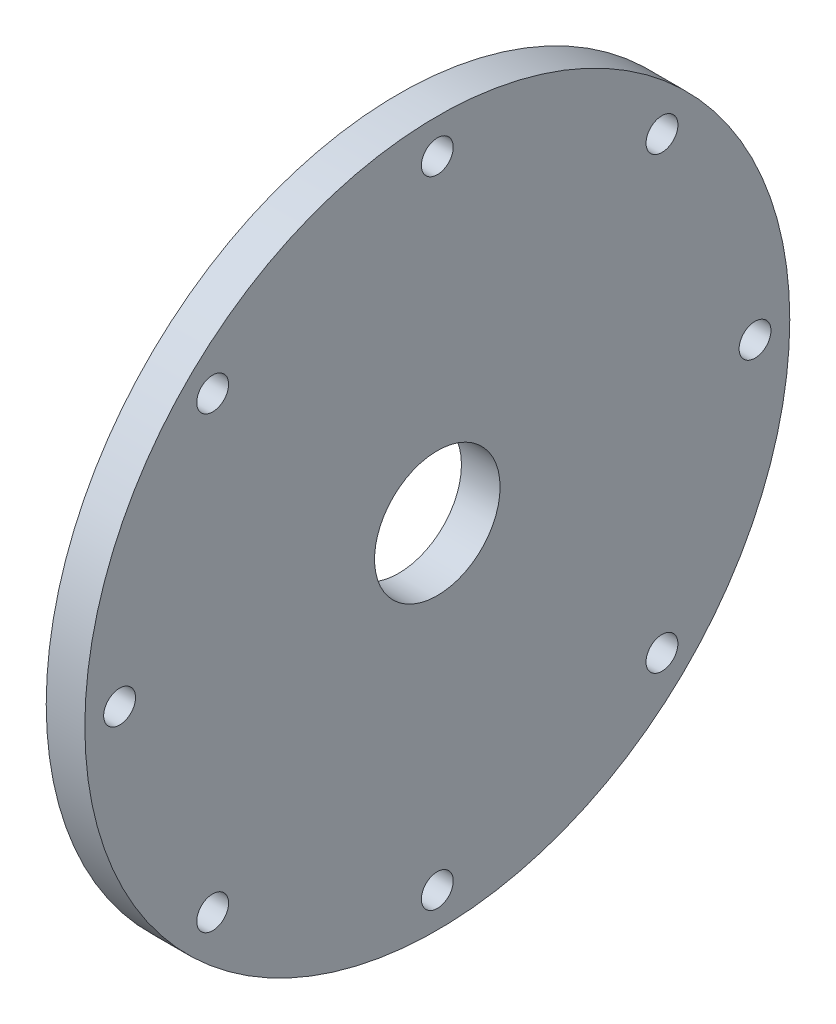
SolidWorks part; units mm, degrees
material "聚脂树脂"
ref_plane "前视基准面" through (0, 0, 0) normal (0, 0, 1) x (1, 0, 0)
ref_plane "上视基准面" through (0, 0, 0) normal (0, 1, 0) x (1, 0, 0)
ref_plane "右视基准面" through (0, 0, 0) normal (1, 0, 0) x (0, 0, -1)
sketch "草图1" plane through (0, 0, 0) normal (1, 0, 0) x (0, 0, -1)
  circle A0 centre (0, 0) radius 36.5
  circle A1 centre (0, 0) radius 6.5
  dimension "D1" = 73
  dimension "D2" = 13
extrude "凸台-拉伸1" add sketch "草图1" along normal blind 4
sketch "草图2" plane through (4, 0, 0) normal (1, 0, 0) x (0, 0, -1)
  line L0 (0, 0) -> (32.9, 0)
  circle A0 centre (32.9, 0) radius 1.65
  circle A1 centre (23.2638, -23.2638) radius 1.65
  circle A2 centre (0, -32.9) radius 1.65
  circle A3 centre (-23.2638, -23.2638) radius 1.65
  circle A4 centre (-32.9, 0) radius 1.65
  circle A5 centre (-23.2638, 23.2638) radius 1.65
  circle A6 centre (0, 32.9) radius 1.65
  circle A7 centre (23.2638, 23.2638) radius 1.65
  point P20 (0, 0)
  dimension "D1" = 3.3
  dimension "D3" = 8
  dimension "D2" = 32.9
extrude "切除-拉伸1" cut sketch "草图2" against normal blind 6 contours A5 | A6 | A7 | A0 | A1 | A2 | A3 | A4
